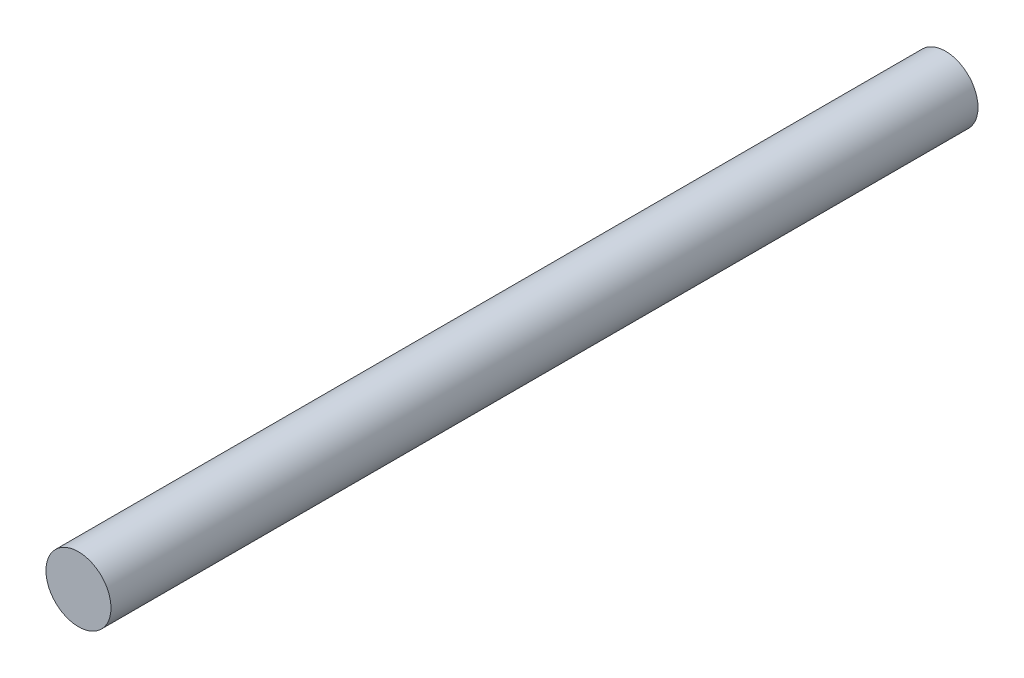
SolidWorks part; units mm, degrees
ref_plane "前视基准面" through (0, 0, 0) normal (0, 0, 1) x (1, 0, 0)
ref_plane "上视基准面" through (0, 0, 0) normal (0, 1, 0) x (1, 0, 0)
ref_plane "右视基准面" through (0, 0, 0) normal (1, 0, 0) x (0, 0, -1)
other "Configuration Table"
sketch "草图1" plane through (0, 0, 0) normal (0, 0, 1) x (1, 0, 0)
  circle A0 centre (0, 0) radius 1.5
extrude "凸台-拉伸1" add sketch "草图1" along normal mid plane 40
